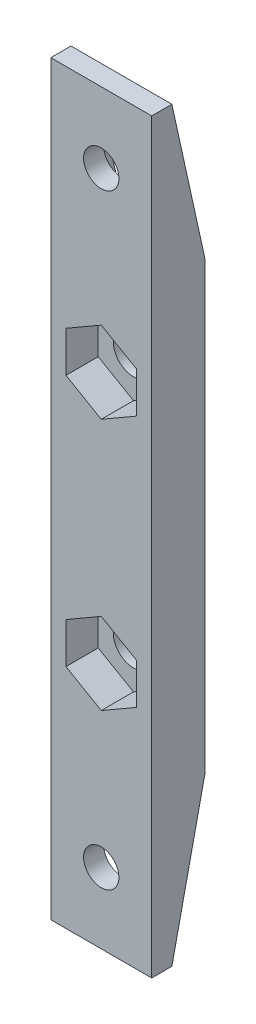
SolidWorks part; units mm, degrees
ref_plane "Front Plane" through (0, 0, 0) normal (0, 0, 1) x (1, 0, 0)
ref_plane "Top Plane" through (0, 0, 0) normal (0, 1, 0) x (1, 0, 0)
ref_plane "Right Plane" through (0, 0, 0) normal (1, 0, 0) x (0, 0, -1)
sketch "Sketch1" plane through (0, 0, 0) normal (0, 0, 1) x (1, 0, 0)
  line L1 (0, 0) -> (10, 0)
  line L2 (0, 0) -> (0, 50)
  line L3 (0, 50) -> (10, 50)
  line L4 (10, 0) -> (10, 50)
  dimension "D1" = 10
  dimension "D2" = 50
extrude "Boss-Extrude1" add sketch "Sketch1" along normal blind 5.3
sketch "Sketch2" plane through (0, 0, 5.3) normal (0, 0, 1) x (1, 0, 0)
  line L0 (5, 50) -> (5, 0) construction
  line L1 (10, 50) -> (0, 50) construction
  line L2 (0, 0) -> (10, 0) construction
  line L4 (8.5, 14.5207) -> (5, 16.5415)
  line L5 (5, 16.5415) -> (1.5, 14.5207)
  line L6 (1.5, 14.5207) -> (1.5, 10.4793)
  line L7 (1.5, 10.4793) -> (5, 8.4585)
  line L8 (5, 8.4585) -> (8.5, 10.4793)
  line L9 (8.5, 10.4793) -> (8.5, 14.5207)
  line L10 (8.5, 39.5207) -> (5, 41.5415)
  line L11 (5, 41.5415) -> (1.5, 39.5207)
  line L12 (1.5, 39.5207) -> (1.5, 35.4793)
  line L13 (1.5, 35.4793) -> (5, 33.4585)
  line L14 (5, 33.4585) -> (8.5, 35.4793)
  line L15 (8.5, 35.4793) -> (8.5, 39.5207)
  circle A1 centre (5, 37.5) radius 3.5 construction
  circle A2 centre (5, 12.5) radius 3.5 construction
  dimension "D1" = 7
  dimension "D2" = 12.5
  dimension "D3" = 25
extrude "Cut-Extrude1" cut sketch "Sketch2" against normal blind 3.2
sketch "Sketch3" plane through (0, 0, 2.1) normal (0, 0, 1) x (1, 0, 0)
  line L0 (1.5, 39.5207) -> (1.5, 35.4793) construction
  line L2 (5, 33.4585) -> (8.5, 35.4793) construction
  circle A0 centre (5, 37.5) radius 2
  circle A1 centre (5, 12.5) radius 2
  dimension "D3" = 4
  dimension "D1" = 3.5
  dimension "D2" = 3.5
  dimension "D4" = 25
extrude "Cut-Extrude2" cut sketch "Sketch3" against normal blind 8
sketch "Sketch4" plane through (0, 50, 0) normal (0, 1, 0) x (1, 0, 0)
  line L0 (10, -5.3) -> (0, -5.3) construction
  line L1 (10, 0) -> (0, 0)
  line L2 (10, 0) -> (10, -5.3)
  line L3 (10, -5.3) -> (0, -5.3)
  line L4 (0, 0) -> (0, -5.3)
extrude "Boss-Extrude2" add sketch "Sketch4" along normal blind 12
sketch "Sketch5" plane through (0, 0, 0) normal (0, -1, 0) x (1, 0, 0)
  line L1 (0, 5.3) -> (10, 5.3)
  line L2 (0, 5.3) -> (0, 0)
  line L3 (0, 0) -> (10, 0)
  line L4 (10, 5.3) -> (10, 0)
extrude "Boss-Extrude3" add sketch "Sketch5" along normal blind 12
sketch "Sketch6" plane through (0, 0, 0) normal (-1, 0, 0) x (0, 0, 1)
  line L0 (3.3, 62) -> (0, 47)
  line L1 (0, 62) -> (5.3, 62) construction
  line L2 (0, 62) -> (0, -12) construction
  line L3 (0, 47) -> (0, 62)
  line L4 (0, 62) -> (3.3, 62)
  line L6 (0, -12) -> (3.3, -12)
  line L8 (3.3, -12) -> (0, 3)
  line L9 (0, 3) -> (0, -12)
  dimension "D1" = 3.3
  dimension "D2" = 15
  dimension "D3" = 3.3
  dimension "D4" = 15
extrude "Cut-Extrude3" cut sketch "Sketch6" against normal blind 12
sketch "Sketch8" plane through (0, 0, 0) normal (0, 0, -1) x (-1, 0, 0)
  line L0 (-10, 62) -> (0, 62) construction
  line L1 (-2, 62) -> (-8, 62)
  line L2 (-2, 62) -> (-2, 49)
  line L3 (-2, 49) -> (-8, 49)
  line L4 (-8, 62) -> (-8, 49)
  line L5 (0, 47) -> (0, 62) construction
  line L6 (-10, 47) -> (-10, 62) construction
  line L7 (-10, 47) -> (0, 47) construction
  line L8 (-10, -12) -> (0, -12) construction
  line L9 (-2, 1) -> (-8, 1)
  line L10 (-2, 1) -> (-2, -12)
  line L11 (-2, -12) -> (-8, -12)
  line L12 (-8, 1) -> (-8, -12)
  line L13 (0, -12) -> (0, 3) construction
  line L14 (-10, -12) -> (-10, 3) construction
  line L15 (-10, 3) -> (0, 3) construction
  dimension "D1" = 2
  dimension "D2" = 2
  dimension "D3" = 2
  dimension "D4" = 2
  dimension "D5" = 2
  dimension "D6" = 2
extrude "Cut-Extrude4" cut sketch "Sketch8" against normal blind 3.3
sketch "Sketch9" plane through (0, 0, 3.3) normal (0, 0, -1) x (-1, 0, 0)
  line L0 (-2, 62) -> (-8, 62) construction
  line L4 (0, 47) -> (0, 62) construction
  line L7 (-8, -12) -> (-2, -12) construction
  line L8 (0, -12) -> (0, 3) construction
  circle A0 centre (-5, -5) radius 1.75
  circle A1 centre (-5, 55) radius 1.75
  point P6 (0, 0)
  point P8 (0, 54.4587)
  point P10 (0, 0)
  dimension "D3" = 3.5
  dimension "D6" = 3.5
  dimension "D1" = 7
  dimension "D2" = 5
  dimension "D4" = 7
  dimension "D5" = 5
extrude "Cut-Extrude5" cut sketch "Sketch9" against normal blind 3.3
